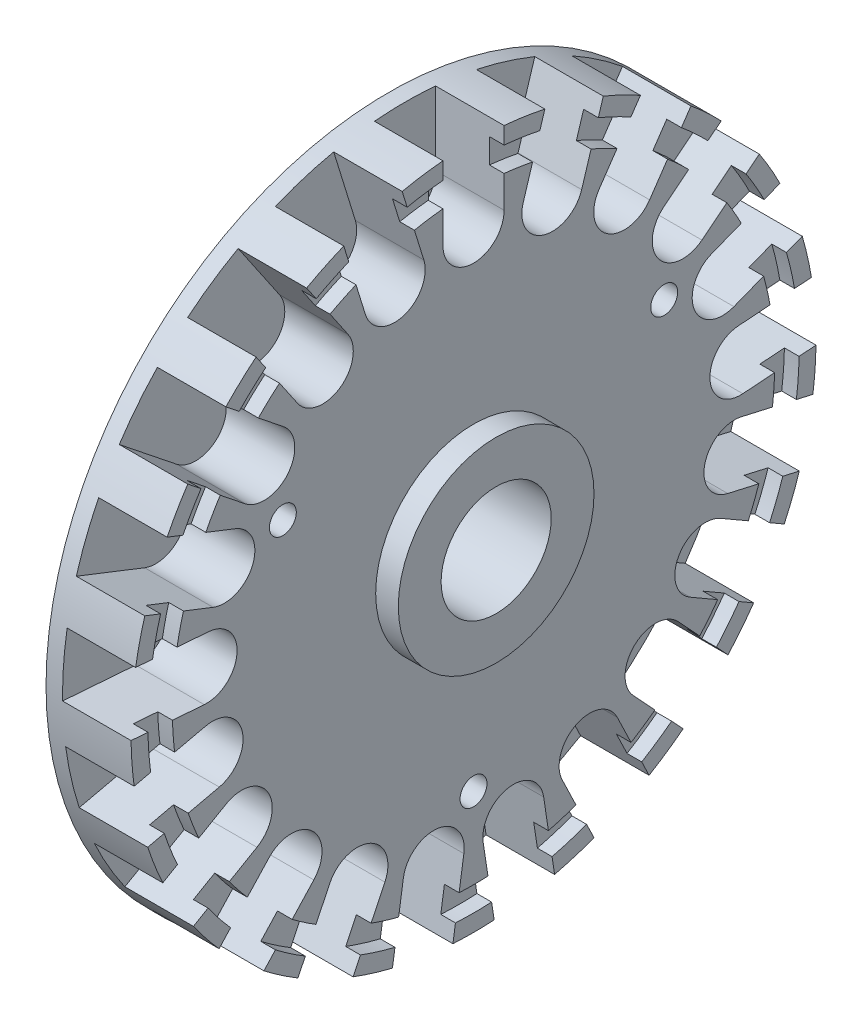
SolidWorks part; units mm, degrees
material "6061 Alloy"
ref_plane "Front" through (0, 0, 0) normal (0, 0, 1) x (1, 0, 0)
ref_plane "Top" through (0, 0, 0) normal (0, 1, 0) x (1, 0, 0)
ref_plane "Right" through (0, 0, 0) normal (1, 0, 0) x (0, 0, -1)
sketch "Horiz & Vert Axis" plane through (0, 0, 0) normal (1, 0, 0) x (0, 0, -1)
  line L0 (-1000, 0) -> (49000, 0) construction
  line L1 (0, -1000) -> (0, 49000) construction
sketch "Sketch2" plane through (0, 0, 0) normal (0, 0, 1) x (1, 0, 0)
  line L0 (0, 4.5) -> (10, 4.5)
  line L2 (10, 28) -> (0, 28)
  line L3 (0, 28) -> (0, 4.5)
  line L4 (10, 28) -> (10, 26.62)
  line L5 (10, 26.62) -> (8.8, 26.62)
  line L6 (8.8, 26.62) -> (8.8, 24.62)
  line L7 (8.8, 24.62) -> (10, 24.62)
  line L8 (10, 24.62) -> (10, 4.5)
  line L9 (10, 24.62) -> (10, 26.62) construction
  line L10 (-52.7486, 0) -> (52.7486, 0) construction
  point P12 (10, 25.62)
  point P16 (0, 0)
  dimension "D1" = 10
  dimension "D3" = 1.38
  dimension "D4" = 2
  dimension "D5" = 1.2
  dimension "D6" = 4.5
  dimension "D2" = 28
revolve "Revolve1" add sketch "Sketch2" angle 360 about L10
sketch "Sketch4" plane through (10, 0, 0) normal (1, 0, 0) x (0, 0, -1)
  line L1 (-2.4997, 27.8882) -> (-2.5, 21.8882)
  line L2 (2.4997, 27.8882) -> (2.5, 21.8882)
  line L4 (0, -201000) -> (0, 249000) construction
  circle A0 centre (0, 0) radius 28 construction
  arc A1 (-2.5, 21.8882) -> (2.5, 21.8882) centre (0, 21.8881) ccw
  arc A2 (-2.4997, 27.8882) -> (2.4997, 27.8882) centre (0, 27.8881) cw
  dimension "D3" = 2.5
  dimension "D1" = 6
  dimension "D2" = 5
extrude "Cut-Extrude1" cut sketch "Sketch4" against normal blind 6.5
pattern_circular "CirPattern1" count 21 over 360 about axis through (0, 0, 0) along (1, 0, 0) of "Cut-Extrude1"
sketch "Sketch6" plane through (10, 0, 0) normal (1, 0, 0) x (0, 0, -1)
  circle A0 centre (0, 0) radius 8
  circle A1 centre (0, 0) radius 4.5
  circle A2 centre (0, 0) radius 4.5 construction
  dimension "D1" = 16
extrude "Boss-Extrude1" add sketch "Sketch6" along normal blind 1.85
hole_wizard "M2 Clearance Hole1" positions "Sketch7" profile "Sketch8" hole size "M2" standard "ANSI Metric" end condition through all
sketch "Sketch7" plane through (0, 0, 0) normal (-1, 0, 0) x (0, 0, 1)
  line L9 (0, 0) -> (0, -18) construction
  line L11 (0, 0) -> (-15.5885, 9) construction
  line L12 (0, 0) -> (15.5885, 9) construction
  line L14 (0, -201000) -> (0, 249000) construction
  point P20 (0, 0)
  point P73 (0, -18)
  point P79 (-15.5885, 9)
  point P80 (15.5885, 9)
  dimension "D1" = 3
sketch "Sketch8" plane through (0, 0, 0) normal (0, 1, 0) x (0, 0, 1)
  line L0 (0, 0) -> (0, 11.85)
  line L1 (0, 11.85) -> (1.1, 11.85)
  line L2 (1.1, 11.85) -> (1.1, 0)
  line L5 (1.1, 0) -> (0, 0)
  line L11 (0, -6.35) -> (0, 107.95) construction
  dimension "Thru Hole Dia." = 2.2
  dimension "Thru Hole Depth" = 11.85
sketch "Sketch10" plane through (0, 0, 0) normal (-1, 0, 0) x (0, 0, 1)
  circle A0 centre (0, 0) radius 28
extrude "Cut-Extrude2" cut sketch "Sketch10" against normal blind 1.8
sketch "Sketch11" plane through (3.5, 0, 0) normal (1, 0, 0) x (0, 0, -1)
  circle A0 centre (0, 0) radius 28
  dimension "D1" = 56
extrude "Boss-Extrude2" add sketch "Sketch11" along normal blind 0.9
sketch "Sketch16" plane through (1.8, 0, 0) normal (-1, 0, 0) x (0, 0, 1)
  circle A0 centre (0, 0) radius 28
  dimension "D1" = 56
extrude "Cut-Extrude4" cut sketch "Sketch16" against normal blind 1.25
sketch "Sketch21" plane through (4.4, 0, 0) normal (1, 0, 0) x (0, 0, -1)
  circle A0 centre (0, 0) radius 4.5
  circle A1 centre (0, -18) radius 1.1
  circle A2 centre (-15.5885, 9) radius 1.1
  circle A3 centre (15.5885, 9) radius 1.1
  dimension "D1" = 9
  dimension "D2" = 2.2
  dimension "D3" = 2.2
  dimension "D4" = 2.2
extrude "Cut-Extrude5" cut sketch "Sketch21" along normal through all and the other way through all contours A0 | A2 | A3 | A1
equation "\"D6@Sketch2\"=9/2"
